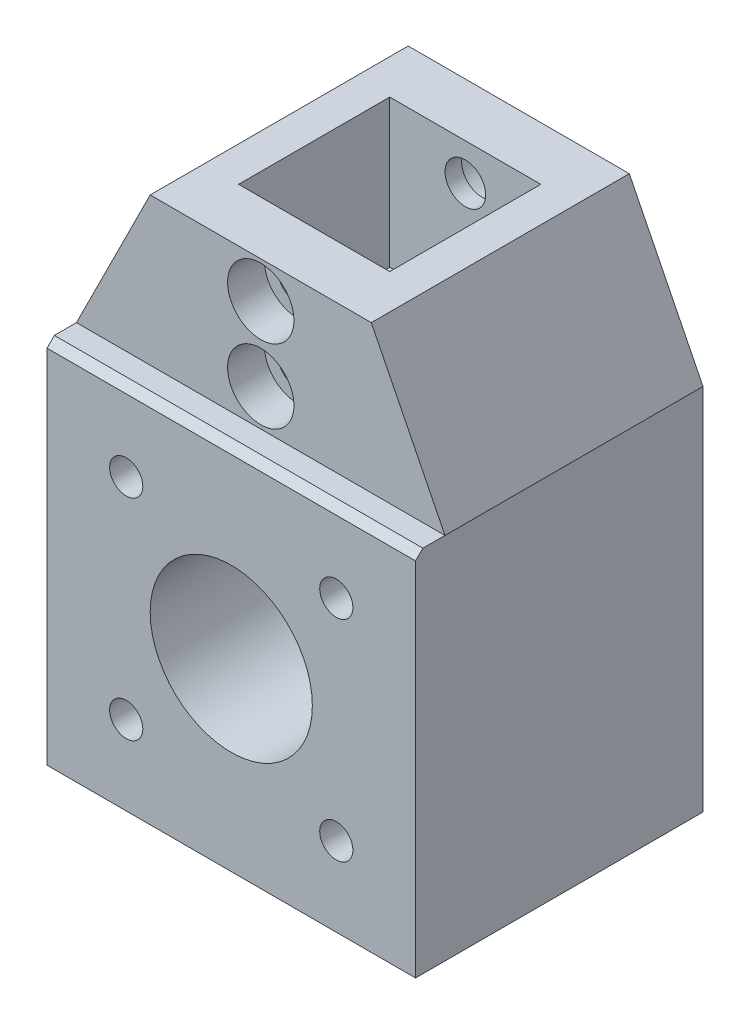
SolidWorks part; units mm, degrees
ref_plane "Front Plane" through (0, 0, 0) normal (0, 0, 1) x (1, 0, 0)
ref_plane "Top Plane" through (0, 0, 0) normal (0, 1, 0) x (1, 0, 0)
ref_plane "Right Plane" through (0, 0, 0) normal (1, 0, 0) x (0, 0, -1)
sketch "Sketch1" plane through (0, 0, 0) normal (0, 0, 1) x (1, 0, 0)
  line L0 (-25, 25) -> (-15, 45)
  line L1 (25, -25) -> (-25, -25)
  line L2 (25, -25) -> (25, 25)
  line L4 (-25, -25) -> (-25, 25)
  line L5 (25, -25) -> (-25, 25) construction
  line L6 (25, 25) -> (-25, -25) construction
  line L7 (-15, 45) -> (15, 45)
  line L8 (15, 45) -> (25, 25)
  circle A0 centre (0, 0) radius 11
  point P0 (0, 0)
  point P6 (0, 45)
  dimension "D3" = 22
  dimension "D1" = 30
  dimension "D2" = 50
  dimension "D4" = 70
extrude "Body" add sketch "Sketch1" along normal mid plane 35
sketch "Sketch4" plane through (0, 45, 0) normal (0, 1, 0) x (1, 0, 0)
  line L1 (10.25, -10.25) -> (-10.25, -10.25)
  line L2 (10.25, -10.25) -> (10.25, 10.25)
  line L3 (10.25, 10.25) -> (-10.25, 10.25)
  line L4 (-10.25, -10.25) -> (-10.25, 10.25)
  line L5 (10.25, -10.25) -> (-10.25, 10.25) construction
  line L6 (10.25, 10.25) -> (-10.25, -10.25) construction
  point P0 (0, 0)
  dimension "D1" = 20.5
extrude "Profil_Hole" cut sketch "Sketch4" against normal blind 20
hole_wizard "M4 Clearance Hole1" positions "Sketch7" profile "Sketch6" hole size "M4" standard "ANSI Metric" end condition through all
sketch "Sketch7" plane through (0, 0, -17.5) normal (0, 0, -1) x (-1, 0, 0)
  line L1 (14.25, -14.25) -> (-14.25, -14.25) construction
  line L2 (14.25, -14.25) -> (14.25, 14.25) construction
  line L3 (14.25, 14.25) -> (-14.25, 14.25) construction
  line L4 (-14.25, -14.25) -> (-14.25, 14.25) construction
  line L5 (14.25, -14.25) -> (-14.25, 14.25) construction
  line L6 (14.25, 14.25) -> (-14.25, -14.25) construction
  point P1 (0, 0)
  point P2 (-14.25, 14.25)
  point P97 (14.25, -14.25)
  point P98 (14.25, 14.25)
  point P99 (-14.25, -14.25)
  dimension "D1" = 28.5
sketch "Sketch6" plane through (0, 0, -17.5) normal (1, 0, 0) x (0, 1, 0)
  line L0 (0, 0) -> (0, 35)
  line L1 (0, 35) -> (2.25, 35)
  line L2 (2.25, 35) -> (2.25, 0)
  line L5 (2.25, 0) -> (0, 0)
  line L11 (0, -6.35) -> (0, 107.95) construction
  dimension "Thru Hole Dia." = 4.5
  dimension "Thru Hole Depth" = 35
hole_wizard "M5 Clearance Hole1" positions "Sketch8" profile "Sketch9" hole size "M5" standard "ANSI Metric" end condition through all
sketch "Sketch8" plane through (0, 0, -17.5) normal (0, 0, -1) x (-1, 0, 0)
  line L0 (0, 40) -> (0, 30) construction
  line L2 (-15, 45) -> (15, 45) construction
  point P0 (0, 40)
  point P3 (0, 30)
  dimension "D1" = 5
  dimension "D2" = 10
sketch "Sketch9" plane through (0, 40, -17.5) normal (1, 0, 0) x (0, 1, 0)
  line L0 (0, 0) -> (0, 35)
  line L1 (0, 35) -> (2.75, 35)
  line L2 (2.75, 35) -> (2.75, 0)
  line L5 (2.75, 0) -> (0, 0)
  line L11 (0, -6.35) -> (0, 107.95) construction
  dimension "Thru Hole Dia." = 5.5
  dimension "Thru Hole Depth" = 35
sketch "Sketch10" plane through (0, 0, 17.5) normal (0, 0, 1) x (1, 0, 0)
  line L1 (25, -25) -> (-25, -25)
  line L2 (25, -25) -> (25, 25)
  line L3 (25, 25) -> (-25, 25)
  line L4 (-25, -25) -> (-25, 25)
  line L5 (25, -25) -> (-25, 25) construction
  line L6 (25, 25) -> (-25, -25) construction
  circle A0 centre (-14.25, -14.25) radius 2.25 construction
  circle A1 centre (14.25, -14.25) radius 2.25 construction
  circle A2 centre (14.25, 14.25) radius 2.25 construction
  circle A3 centre (0, 0) radius 11 construction
  circle A4 centre (-14.25, 14.25) radius 2.25 construction
  circle A5 centre (-14.25, -14.25) radius 2.25
  circle A6 centre (14.25, -14.25) radius 2.25
  circle A7 centre (14.25, 14.25) radius 2.25
  circle A8 centre (0, 0) radius 11
  circle A9 centre (-14.25, 14.25) radius 2.25
  point P0 (0, 0)
extrude "Elevation" add sketch "Sketch10" along normal blind 4
sketch "Sketch11" plane through (0, 0, -17.5) normal (0, 0, -1) x (-1, 0, 0)
  line L0 (0, -1000) -> (0, 49000) construction
  circle A0 centre (-18, 0) radius 3.2
  circle A1 centre (18, 0) radius 3.2
  dimension "D1" = 6.4
  dimension "D2" = 18
extrude "Inserts_Holes" cut sketch "Sketch11" against normal blind 9.5
sketch "Sketch12" plane through (0, 0, -17.5) normal (0, 0, -1) x (-1, 0, 0)
  circle A0 centre (0, 40) radius 4.5
  circle A1 centre (0, 30) radius 4.5
  dimension "D1" = 9
extrude "M5_Vis_Place" cut sketch "Sketch12" against normal blind 5
mirror "Mirror1" about plane through (0, 0, 0) normal (0, 0, 1) of "M5_Vis_Place"
sketch "Sketch13" plane through (0, 0, -17.5) normal (0, 0, -1) x (-1, 0, 0)
  circle A0 centre (-14.25, 14.25) radius 3.75
  circle A1 centre (14.25, 14.25) radius 3.75
  circle A2 centre (14.25, -14.25) radius 3.75
  circle A3 centre (-14.25, -14.25) radius 3.75
  dimension "D1" = 7.5
extrude "M4_Screw_Place" cut sketch "Sketch13" against normal blind 4
chamfer "Chamfer1" distance 1 angle 45 1 edges at (0, 25, 21.5)
